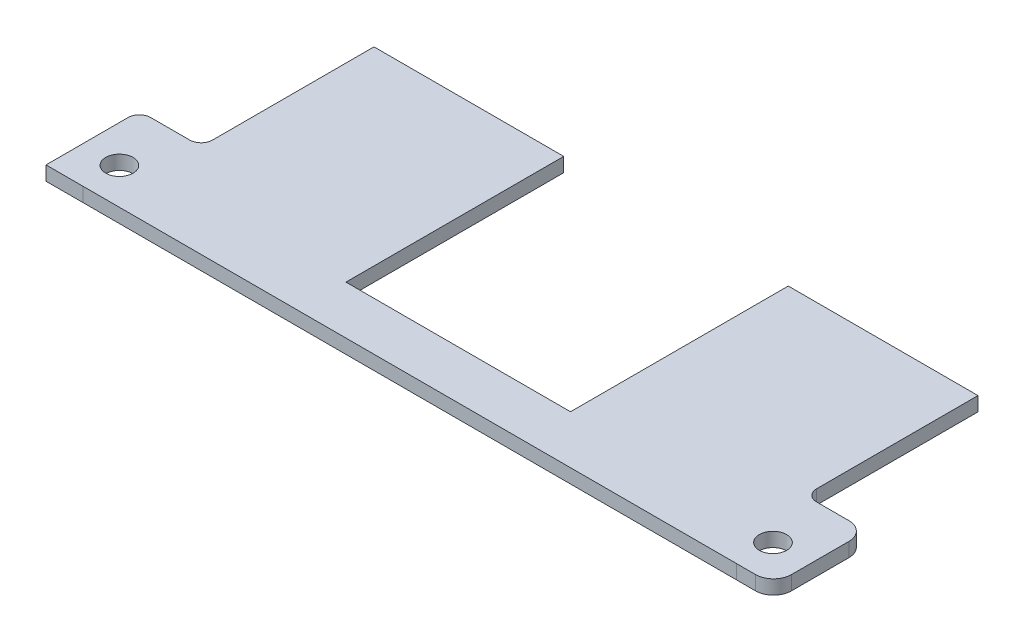
SolidWorks part; units mm, degrees
material "Copper"
ref_plane "Front Plane" through (0, 0, 0) normal (0, 0, 1) x (1, 0, 0)
ref_plane "Top Plane" through (0, 0, 0) normal (0, 1, 0) x (1, 0, 0)
ref_plane "Right Plane" through (0, 0, 0) normal (1, 0, 0) x (0, 0, -1)
sketch "Sketch1" plane through (0, 0, 0) normal (0, 1, 0) x (1, 0, 0)
  line L0 (38.8513, -40.0144) -> (36.7273, -40.0144)
  line L1 (0, 0) -> (0, -40.0124) construction
  line L2 (-12.1487, -17.8713) -> (-12.1487, -10.3704)
  line L3 (-36.0247, -40.0144) -> (-36.0247, -40.0124)
  line L4 (36.7273, -40.0144) -> (36.7273, -40.0124)
  line L5 (-36.0247, -40.0144) -> (-40.1487, -40.0144)
  line L8 (12.8513, -10.3704) -> (12.8513, -17.8713)
  line L11 (30.3773, -40.0124) -> (36.7273, -40.0124)
  line L12 (40.8513, -38.0144) -> (40.8513, -31.6159)
  line L13 (38.8513, -29.6159) -> (35.2463, -29.6159)
  line L14 (33.9763, -28.3459) -> (33.9763, -10.3704)
  line L20 (-33.2737, -10.3704) -> (-33.2737, -28.3459)
  line L21 (-34.5437, -29.6159) -> (-38.8787, -29.6159)
  line L22 (-40.1487, -30.8859) -> (-40.1487, -40.0144)
  line L23 (-36.0247, -40.0124) -> (-29.6747, -40.0124)
  line L24 (-29.6747, -40.0124) -> (30.3773, -40.0124)
  line L25 (-12.1487, -34.6159) -> (12.8513, -34.6159)
  line L26 (-12.1487, -17.8713) -> (-12.1487, -34.6159)
  line L27 (12.8513, -17.8713) -> (12.8513, -34.6159)
  line L28 (-33.2737, -10.3704) -> (-12.1487, -10.3704)
  line L29 (12.8513, -10.3704) -> (33.9763, -10.3704)
  circle A0 centre (-36.0247, -35.9659) radius 1.524
  circle A1 centre (36.7273, -35.9479) radius 1.524
  arc A2 (38.8513, -40.0144) -> (40.8513, -38.0144) centre (38.8513, -38.0144) ccw
  arc A6 (40.8513, -31.6159) -> (38.8513, -29.6159) centre (38.8513, -31.6159) ccw
  arc A7 (33.9763, -28.3459) -> (35.2463, -29.6159) centre (35.2463, -28.3459) ccw
  arc A13 (-34.5437, -29.6159) -> (-33.2737, -28.3459) centre (-34.5437, -28.3459) ccw
  arc A14 (-38.8787, -29.6159) -> (-40.1487, -30.8859) centre (-38.8787, -30.8859) ccw
  point P1 (0, 0)
  dimension "D2" = 4.124
  dimension "D10" = 2
  dimension "D1" = 0.002
  dimension "D3" = 4.124
  dimension "D4" = 21.125
  dimension "D5" = 4.335
  dimension "D6" = 3.605
  dimension "D7" = 24.2455
  dimension "D8" = 21.125
  dimension "D9" = 25
extrude "Boss-Extrude1" add sketch "Sketch1" along normal blind 1.575
sketch "Sketch4" plane through (0, 1.575, 0) normal (0, 1, 0) x (1, 0, 0)
